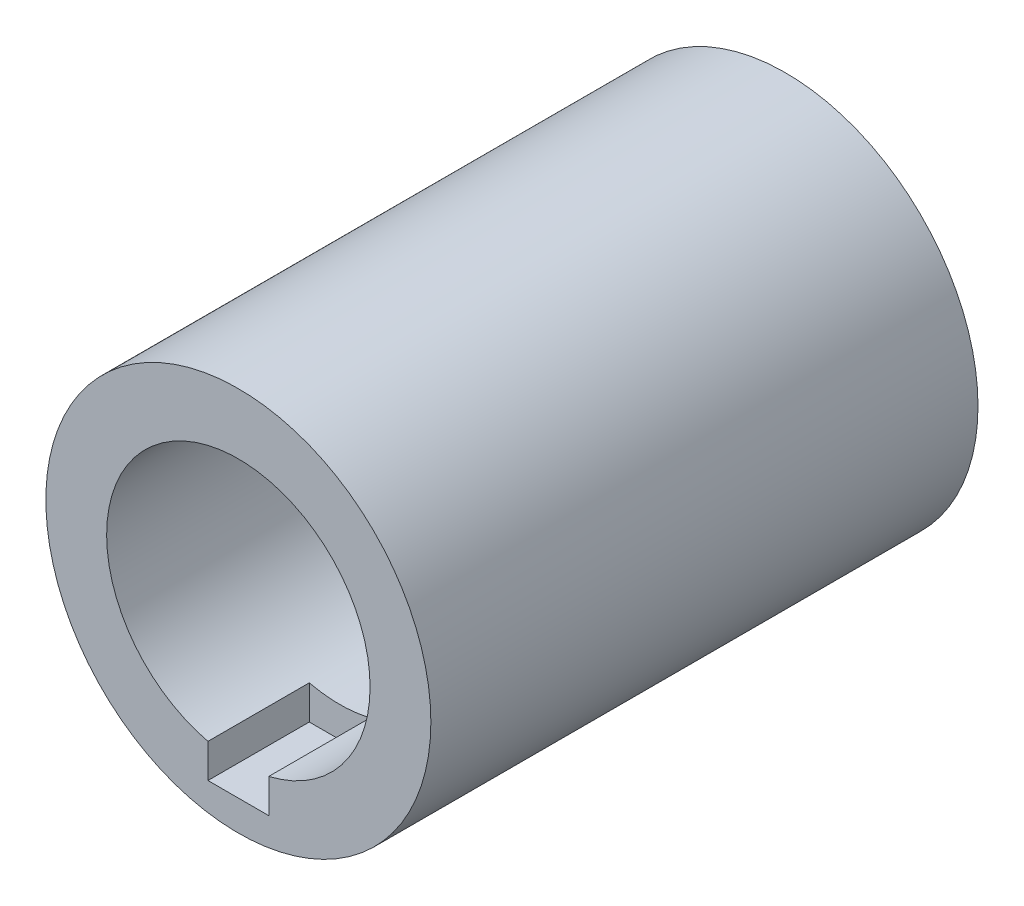
SolidWorks part; units mm, degrees
material "Plain Carbon Steel"
ref_plane "Front Plane" through (0, 0, 0) normal (0, 0, 1) x (1, 0, 0)
ref_plane "Top Plane" through (0, 0, 0) normal (0, 1, 0) x (1, 0, 0)
ref_plane "Right Plane" through (0, 0, 0) normal (1, 0, 0) x (0, 0, -1)
sketch "Sketch1" plane through (0, 0, 0) normal (0, 0, 1) x (1, 0, 0)
  circle A0 centre (0, 0) radius 6.5
  circle A1 centre (0, 0) radius 9.5
  dimension "D1" = 13
  dimension "D2" = 19
extrude "Boss-Extrude1" add sketch "Sketch1" along normal mid plane 27 contours A1 A0
sketch "Sketch2" plane through (0, 0, 0) normal (0, 1, 0) x (1, 0, 0)
  line L0 (0, 0) -> (0, -50000) construction
  line L1 (-9.5, -13.5) -> (9.5, -13.5) construction
  line L2 (-1.5, -8.5) -> (1.5, -8.5)
  line L3 (-1.5, -8.5) -> (-1.5, -13.5)
  line L4 (-1.5, -13.5) -> (1.5, -13.5)
  line L5 (1.5, -8.5) -> (1.5, -13.5)
  line L6 (-1.5, -8.5) -> (1.5, -13.5) construction
  line L7 (-1.5, -13.5) -> (1.5, -8.5) construction
  point P3 (0, -11)
  dimension "D1" = 3
  dimension "5" = 5
extrude "Cut-Extrude1" cut sketch "Sketch2" along normal up to next from offset 8 offset against normal yes
